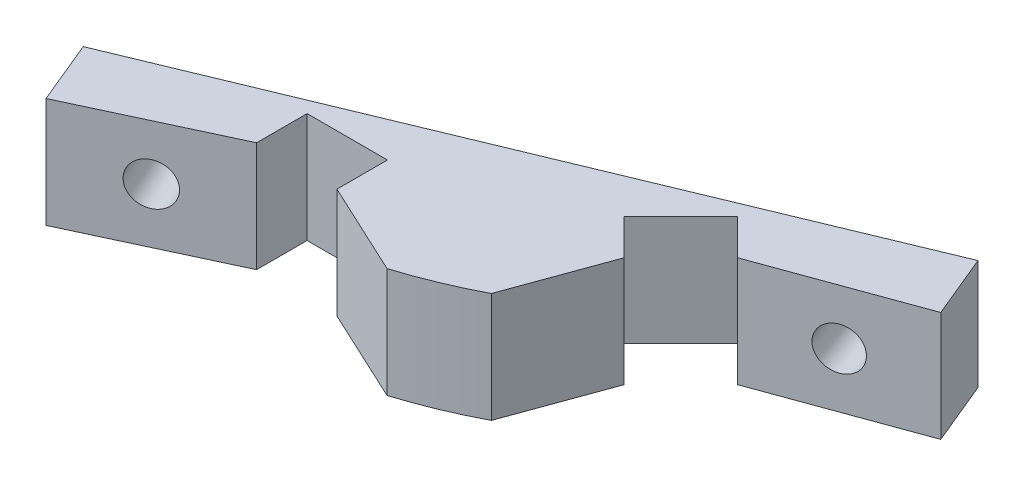
SolidWorks part; units mm, degrees
ref_plane "Front Plane" through (0, 0, 0) normal (0, 0, 1) x (1, 0, 0)
ref_plane "Top Plane" through (0, 0, 0) normal (0, 1, 0) x (1, 0, 0)
ref_plane "Right Plane" through (0, 0, 0) normal (1, 0, 0) x (0, 0, -1)
sketch "Sketch2" plane through (0, 0, 0) normal (0, 1, 0) x (1, 0, 0)
  line L0 (-2.785, -18.89) -> (-2.785, -22.39)
  line L1 (0, 4.23) -> (0, -26.25) construction
  line L2 (0, -18.89) -> (2.785, -18.89)
  line L3 (0, -18.89) -> (-2.785, -18.89)
  line L4 (2.785, -18.89) -> (2.785, -22.39)
  line L5 (2.785, -22.39) -> (9.2872, -25.422)
  line L6 (-2.785, -22.39) -> (-9.2872, -25.422)
  line L7 (27.5342, -10.1701) -> (19.1524, -5.7865)
  line L8 (-9.2872, -25.422) -> (-6.46, -16.3955)
  line L43 (16.3483, -12.1183) -> (18.3176, -10.149)
  line L44 (16.3483, -12.1183) -> (14.379, -14.0876)
  line L45 (14.379, -14.0876) -> (16.8539, -16.5625)
  line L46 (18.3176, -10.149) -> (20.7925, -12.6239)
  line L47 (16.8539, -16.5625) -> (14.4001, -23.3042)
  line L48 (20.7925, -12.6239) -> (27.5342, -10.1701)
  line L50 (11.8909, -24.4772) -> (2.0065, -0.6142) construction
  line L51 (-6.46, -16.3955) -> (19.1524, -5.7865)
  line L54 (-16.8539, -16.5625) -> (-14.4001, -23.3042) [skipped]
  line L55 (-16.3483, -12.1183) -> (-18.3176, -10.149) [skipped]
  line L56 (-18.3176, -10.149) -> (-20.7925, -12.6239) [skipped]
  line L57 (-20.7925, -12.6239) -> (-27.5342, -10.1701) [skipped]
  line L58 (-16.3483, -12.1183) -> (-14.379, -14.0876) [skipped]
  line L59 (-14.379, -14.0876) -> (-16.8539, -16.5625) [skipped]
  line L60 (-26.62, 1.445) -> (-29.652, -5.0572) [skipped]
  line L61 (-23.12, 1.445) -> (-26.62, 1.445) [skipped]
  line L62 (-23.12, 4.23) -> (-23.12, 7.015) [skipped]
  line L63 (-23.12, 4.23) -> (-23.12, 1.445) [skipped]
  line L64 (-26.62, 7.015) -> (-29.652, 13.5172) [skipped]
  line L65 (-23.12, 7.015) -> (-26.62, 7.015) [skipped]
  line L66 (2.785, 27.35) -> (2.785, 30.85) [skipped]
  line L67 (-2.785, 27.35) -> (-2.785, 30.85) [skipped]
  line L68 (-14.379, 22.5476) -> (-16.8539, 25.0225) [skipped]
  line L69 (-16.8539, 25.0225) -> (-14.4001, 31.7642) [skipped]
  line L70 (-20.7925, 21.0839) -> (-27.5342, 18.6301) [skipped]
  line L71 (-18.3176, 18.609) -> (-20.7925, 21.0839) [skipped]
  line L72 (-16.3483, 20.5783) -> (-18.3176, 18.609) [skipped]
  line L73 (-16.3483, 20.5783) -> (-14.379, 22.5476) [skipped]
  line L74 (-2.785, 30.85) -> (-9.2872, 33.882) [skipped]
  line L75 (2.785, 30.85) -> (9.2872, 33.882) [skipped]
  line L76 (16.8539, 25.0225) -> (14.4001, 31.7642) [skipped]
  line L77 (0, 27.35) -> (-2.785, 27.35) [skipped]
  line L78 (0.9081, 27.35) -> (2.785, 27.35) [skipped]
  line L79 (14.379, 22.5476) -> (16.8539, 25.0225) [skipped]
  line L80 (20.7925, 21.0839) -> (27.5342, 18.6301) [skipped]
  line L81 (16.3483, 20.5783) -> (14.379, 22.5476) [skipped]
  line L82 (18.3176, 18.609) -> (20.7925, 21.0839) [skipped]
  line L83 (16.3483, 20.5783) -> (18.3176, 18.609) [skipped]
  line L84 (23.12, 7.015) -> (26.62, 7.015) [skipped]
  line L85 (23.12, 1.445) -> (26.62, 1.445) [skipped]
  line L86 (26.62, 7.015) -> (29.652, 13.5172) [skipped]
  line L87 (23.12, 4.23) -> (23.12, 7.015) [skipped]
  line L88 (23.12, 4.23) -> (23.12, 1.445) [skipped]
  line L89 (26.62, 1.445) -> (29.652, -5.0572) [skipped]
  arc A7 (9.2872, -25.422) -> (14.4001, -23.3042) centre (0, 4.23) ccw
  arc A8 (0, -26.25) -> (9.2872, -25.422) centre (0, 26.25) ccw [skipped]
  arc A9 (14.4001, -23.3042) -> (27.5342, -10.1701) centre (-15.5705, 19.8005) ccw [skipped]
  arc A11 (-27.5342, -10.1701) -> (-14.4001, -23.3042) centre (15.5705, 19.8005) ccw [skipped]
  arc A12 (-29.652, 13.5172) -> (-29.652, -5.0572) centre (22.02, 4.23) ccw [skipped]
  arc A13 (9.2872, 33.882) -> (-9.2872, 33.882) centre (0, -17.79) ccw [skipped]
  arc A14 (-14.4001, 31.7642) -> (-27.5342, 18.6301) centre (15.5705, -11.3405) ccw [skipped]
  arc A15 (27.5342, 18.6301) -> (14.4001, 31.7642) centre (-15.5705, -11.3405) ccw [skipped]
  arc A16 (29.652, -5.0572) -> (29.652, 13.5172) centre (-22.02, 4.23) ccw [skipped]
  point P3 (0, -18.89)
  point P79 (6.3462, -11.091)
  dimension "D1" = 30.48
  dimension "D2" = 8
extrude "Boss-Extrude2" add sketch "Sketch2" along normal blind 7.62
sketch "Sketch15" plane through (0, 7.62, 0) normal (0, 1, 0) x (-1, 0, 0)
  line L0 (-22.2179, 7.3897) -> (7.494, 19.6968)
  line L1 (-27.5342, 10.1701) -> (-19.1524, 5.7865) construction
  line L2 (6.46, 16.3955) -> (9.2872, 25.422) construction
  line L3 (-19.1506, 5.7856) -> (6.4594, 16.3936)
  line L4 (-19.1506, 5.7856) -> (-22.2179, 7.3897)
  line L5 (6.4594, 16.3936) -> (7.494, 19.6968)
  point P8 (-23.3433, 7.9783)
  point P9 (7.8736, 20.9088)
  dimension "D2" = 1.27
  dimension "D3" = 1.27
extrude "Cut-Extrude3" cut sketch "Sketch15" against normal blind 2.159
sketch "Sketch22" plane through (0, 7.62, 0) normal (0, 1, 0) x (1, 0, 0)
  line L0 (11.8909, -24.4772) -> (7.3619, -13.5433) construction
  line L1 (-9.2872, -25.422) -> (-7.494, -19.6968)
  line L2 (-12.7402, -27.0322) -> (-14.5654, -22.6259)
  line L3 (31.1144, -8.867) -> (27.5342, -10.1701)
  line L4 (22.2179, -7.3897) -> (29.2893, -4.4607)
  line L5 (31.1144, -8.867) -> (29.2893, -4.4607)
  line L6 (27.5342, -10.1701) -> (22.2179, -7.3897)
  line L13 (22.2179, -7.3897) -> (-7.494, -19.6968)
  line L14 (-7.494, -19.6968) -> (-9.2872, -25.422)
  line L15 (-9.2872, -25.422) -> (-2.785, -22.39)
  line L16 (-2.785, -22.39) -> (-2.785, -18.89)
  line L17 (-2.785, -18.89) -> (2.785, -18.89)
  line L18 (2.785, -18.89) -> (2.785, -22.39)
  line L19 (2.785, -22.39) -> (9.2872, -25.422)
  line L20 (14.4001, -23.3042) -> (16.8539, -16.5625)
  line L21 (16.8539, -16.5625) -> (14.379, -14.0876)
  line L22 (14.379, -14.0876) -> (18.3176, -10.149)
  line L23 (18.3176, -10.149) -> (20.7925, -12.6239)
  line L24 (20.7925, -12.6239) -> (27.5342, -10.1701)
  line L25 (27.5342, -10.1701) -> (22.2179, -7.3897)
  line L26 (-7.494, -19.6968) -> (-14.5654, -22.6259)
  line L28 (-12.7402, -27.0322) -> (-9.2872, -25.422)
  arc A1 (9.2872, -25.422) -> (14.4001, -23.3042) centre (0, 4.23) ccw
  dimension "D2" = 3.81
  dimension "D1" = 0
extrude "Boss-Extrude5" add sketch "Sketch22" against normal up to surface (7.62 mm away) up to face at (8.9298, 0, 17.3284)
sketch "Sketch26" plane through (8.0784, 0, 17.3243) normal (0.4226, 0, 0.9063) x (0.9063, 0, -0.4226)
  line L0 (-22.9709, 3.81) -> (-11.9865, 3.81) construction
  line L1 (-22.9709, 0) -> (-22.9709, 7.62) construction
  line L2 (-11.9865, 7.62) -> (-11.9865, 0) construction
  line L3 (-17.4787, 7.62) -> (-17.4787, 0) construction
  line L4 (-22.9709, 7.62) -> (-11.9865, 7.62) construction
  line L5 (-22.9709, 0) -> (-11.9865, 0) construction
  circle A0 centre (-17.4787, 3.81) radius 1.4732
  dimension "D1" = 2.9464
extrude "Cut-Extrude4" cut sketch "Sketch26" against normal through all
sketch "Sketch27" plane through (0, 7.62, 0) normal (0, 1, 0) x (-1, 0, 0)
  line L0 (-11.8909, 24.4772) -> (-7.3619, 13.5433) construction
  line L1 (14.5654, 22.6259) -> (-29.2893, 4.4607) construction
  line L2 (-9.6264, 19.0102) -> (-5.9687, 20.5253) construction
  arc A0 (-9.2872, 25.422) -> (-14.4001, 23.3042) centre (0, -4.23) ccw construction
ref_plane "Plane3" through (9.6264, 7.62, 19.0102) normal (-0.9239, 0, 0.3827) x (0.3827, 0, 0.9239)
mirror "Mirror2" about plane through (9.6264, 7.62, 19.0102) normal (-0.9239, 0, 0.3827) of "Cut-Extrude4"
